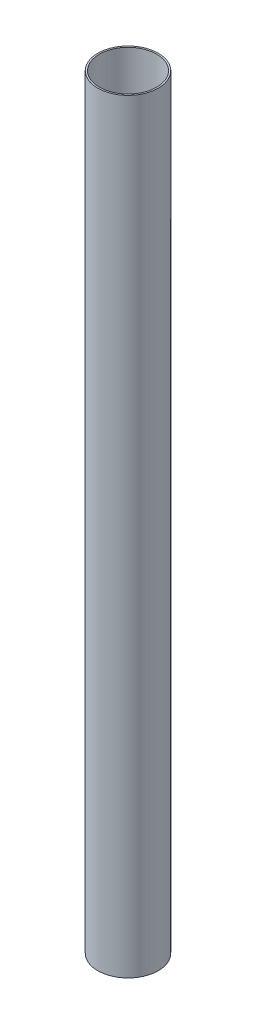
SolidWorks part; units mm, degrees
material "LINER"
ref_plane "Front Plane" through (0, 0, 0) normal (0, 0, 1) x (1, 0, 0)
ref_plane "Top Plane" through (0, 0, 0) normal (0, 1, 0) x (1, 0, 0)
ref_plane "Right Plane" through (0, 0, 0) normal (1, 0, 0) x (0, 0, -1)
sketch "Sketch1" plane through (0, 0, 0) normal (0, 1, 0) x (1, 0, 0)
  circle A0 centre (0, 0) radius 48.26
  circle A1 centre (0, 0) radius 45.72
  dimension "D1" = 96.52
  dimension "D2" = 2.54
extrude "Boss-Extrude1" add sketch "Sketch1" along normal blind 1219.2
